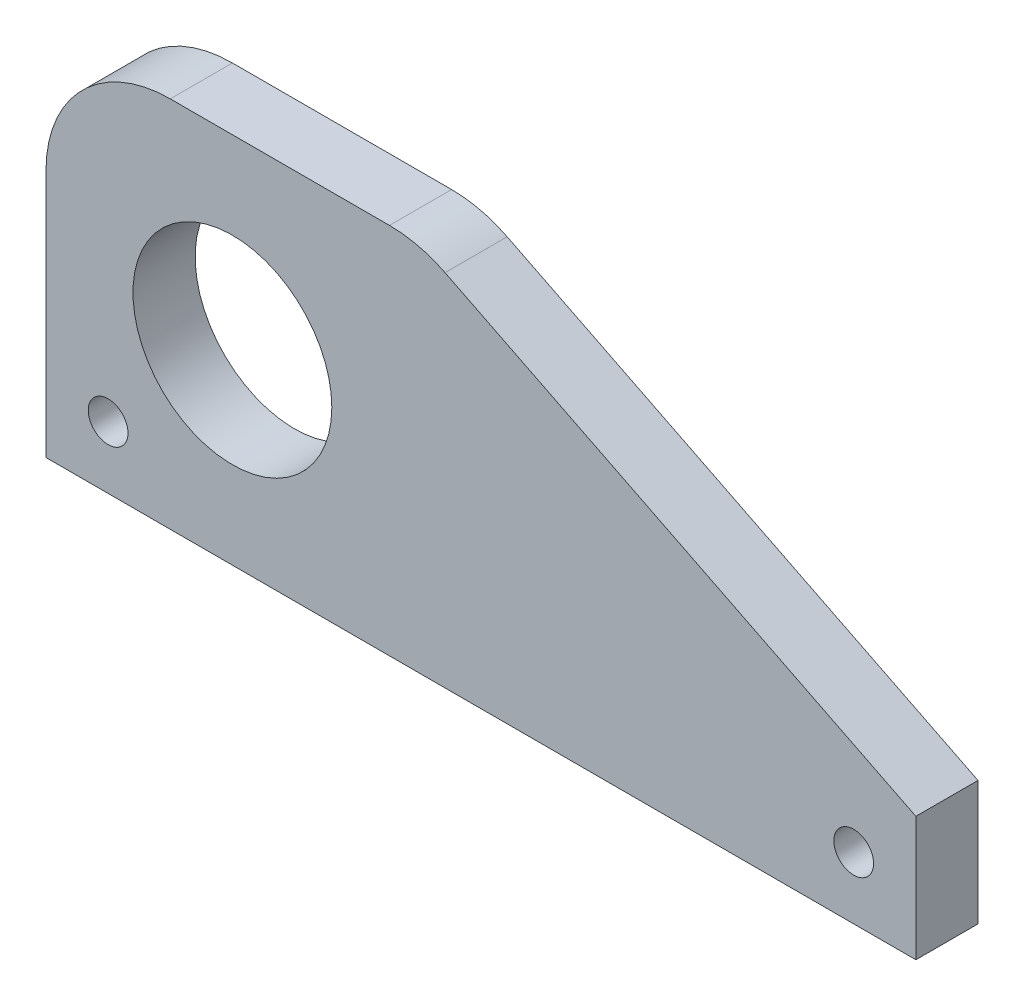
SolidWorks part; units mm, degrees
ref_plane "Front Plane" through (0, 0, 0) normal (0, 0, 1) x (1, 0, 0)
ref_plane "Top Plane" through (0, 0, 0) normal (0, 1, 0) x (1, 0, 0)
ref_plane "Right Plane" through (0, 0, 0) normal (1, 0, 0) x (0, 0, -1)
sketch "ｽｹｯﾁ1" plane through (0, 0, 0) normal (0, 0, 1) x (1, 0, 0)
  line L0 (0, 0) -> (0, 10)
  line L1 (0, 10) -> (0, 30)
  line L2 (0, 30) -> (30, 30)
  line L3 (30, 30) -> (70, 10)
  line L4 (70, 10) -> (70, 0)
  line L5 (70, 0) -> (0, 0)
  circle A0 centre (15, 15) radius 8
  circle A1 centre (5, 5) radius 1.6
  circle A2 centre (65, 5) radius 1.6
  point P13 (15, 30)
  point P14 (35, 0)
  dimension "D5" = 16
  dimension "D6" = 15
  dimension "D9" = 20
  dimension "D10" = 3.2
  dimension "D11" = 5
  dimension "D12" = 5
  dimension "D14" = 3.2
  dimension "D15" = 5
  dimension "D1" = 70
  dimension "D2" = 10
  dimension "D3" = 10
  dimension "D4" = 30
  dimension "D7" = 20
  dimension "D8" = 30
  dimension "D13" = 5
extrude "ﾎﾞｽ - 押し出し1" add sketch "ｽｹｯﾁ1" along normal blind 5
fillet "ﾌｨﾚｯﾄ1" radius 10 2 edges at (30, 30, 2.5) (0, 30, 2.5)
